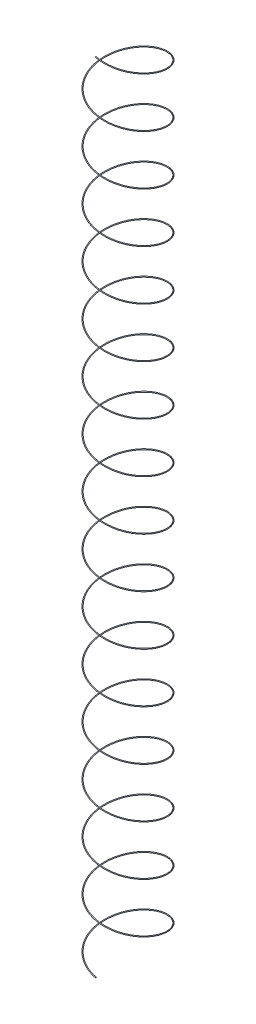
SolidWorks part; units mm, degrees
ref_plane "Front Plane" through (0, 0, 0) normal (0, 0, 1) x (1, 0, 0)
ref_plane "Top Plane" through (0, 0, 0) normal (0, 1, 0) x (1, 0, 0)
ref_plane "Right Plane" through (0, 0, 0) normal (1, 0, 0) x (0, 0, -1)
sketch "Sketch1" plane through (0, 0, 0) normal (0, 1, 0) x (1, 0, 0)
  circle A0 centre (0, 0) radius 20.15
  dimension "D1" = 40.3
curve "Helix/Spiral1" pitch 31.25 height 500 turns 16
sketch "Sketch2" plane through (0, 0, 0) normal (1, 0, 0) x (0, 0, -1)
  circle A0 centre (-20.15, 0) radius 0.25
  dimension "D2" = 0.5
  dimension "D1" = 20.15
sweep "Sweep1" add profiles "Sketch2" path "Helix/Spiral1"
